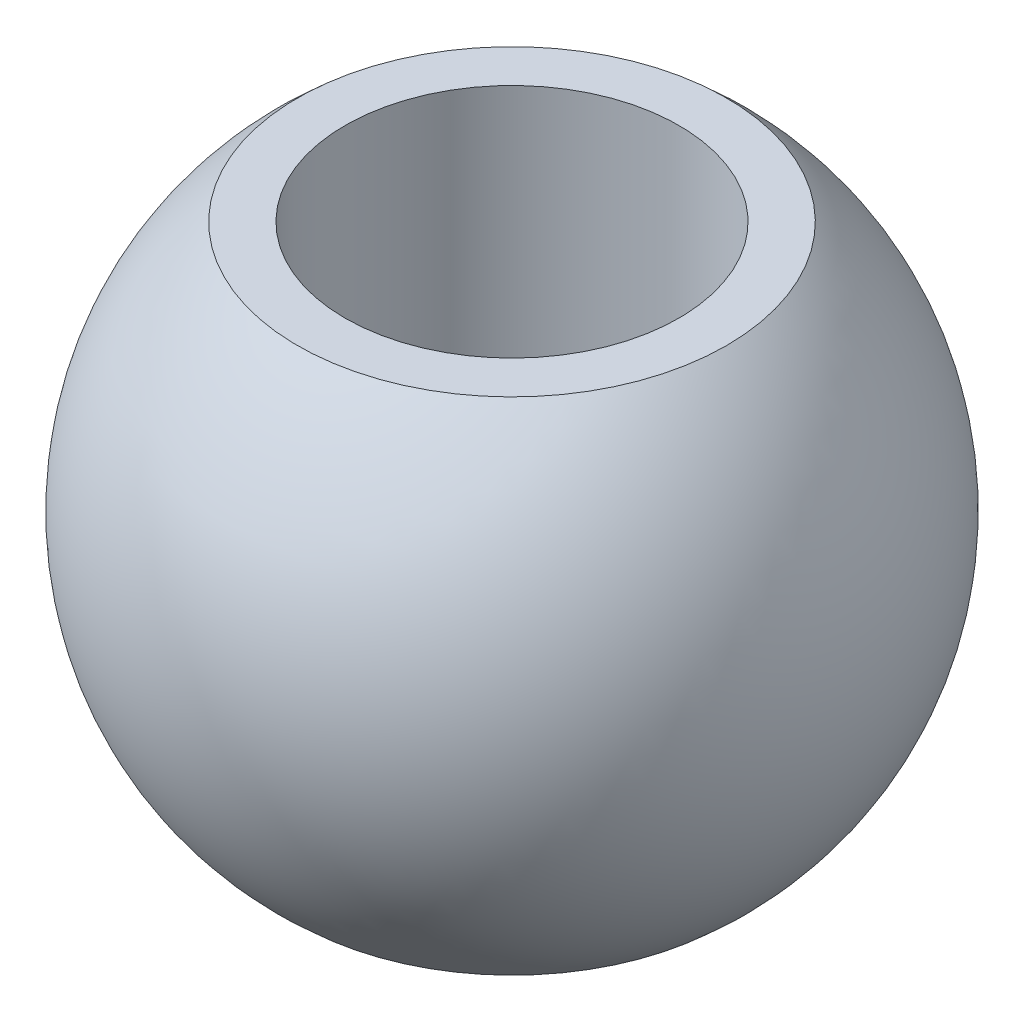
SolidWorks part; units mm, degrees
ref_plane "Front Plane" through (0, 0, 0) normal (0, 0, 1) x (1, 0, 0)
ref_plane "Top Plane" through (0, 0, 0) normal (0, 1, 0) x (1, 0, 0)
ref_plane "Right Plane" through (0, 0, 0) normal (1, 0, 0) x (0, 0, -1)
ref_plane "Plane1" through (0, 0, 0) normal (0, 0, -1) x (-1, 0, 0)
sketch "Sketch1" plane through (0, 0, 0) normal (0, 0, -1) x (-1, 0, 0)
  line L0 (-5.1391, -6) -> (-4, -6)
  line L1 (-4, -6) -> (-4, 6)
  line L2 (-4, 6) -> (-5.1391, 6)
  line L3 (0, -6) -> (0, 6) construction
  arc A0 (-5.1391, 6) -> (-5.1391, -6) centre (0, 0) ccw
revolve "Revolve1" add sketch "Sketch1" angle 360 about L3
